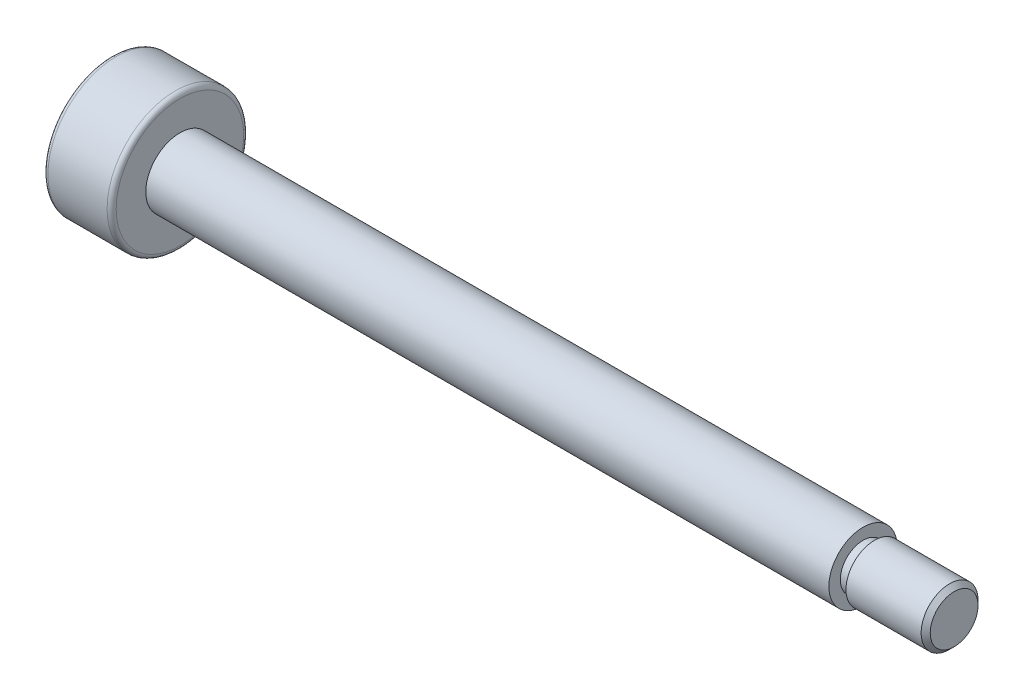
SolidWorks part; units mm, degrees
ref_plane "前视基准面" through (0, 0, 0) normal (0, 0, 1) x (1, 0, 0)
ref_plane "上视基准面" through (0, 0, 0) normal (0, 1, 0) x (1, 0, 0)
ref_plane "右视基准面" through (0, 0, 0) normal (1, 0, 0) x (0, 0, -1)
sketch "草图1" plane through (0, 0, 0) normal (0, 0, 1) x (1, 0, 0)
  line L0 (-18.5, 0) -> (18.5, 0) construction
  line L1 (-18.5, 0) -> (-18.5, 3)
  line L2 (-18.5, 3) -> (-15.5, 3)
  line L3 (-15.5, 3) -> (-15.5, 1.5)
  line L4 (-15.5, 1.5) -> (14.5, 1.5)
  line L5 (14.5, 1.5) -> (14.5, 1.25)
  line L6 (14.5, 1.25) -> (18.5, 1.25)
  line L7 (18.5, 1.25) -> (18.5, 0)
  line L8 (-18.5, 0) -> (18.5, 0)
  dimension "D1" = 3
  dimension "D2" = 6
  dimension "D3" = 2.5
  dimension "D4" = 4
  dimension "D5" = 30
  dimension "D6" = 3
revolve "旋转1" add sketch "草图1" angle 360 about L0
fillet "圆角1" radius 0.2 2 edges at (-15.5, 0, 3) (-18.5, 0, 3)
chamfer "倒角1" distance 0.2 angle 45 1 edges at (18.5, 0, 1.25)
sketch "草图3" plane through (0, 0, 0) normal (0, 0, 1) x (1, 0, 0)
  line L0 (14.5, 0) -> (18.3, 0) construction
  line L1 (14.5, -1.25) -> (14.5, 1.25) construction
  line L2 (18.3, 1.25) -> (18.3, -1.25) construction
  line L3 (14.5, -1.5) -> (14.5, 1.5) construction
  line L4 (14.5, 1.25) -> (15, 1.25)
  line L5 (14.5, 1.25) -> (14.5, 1)
  line L6 (14.5, 1) -> (15, 1)
  line L7 (15, 1.25) -> (15, 1)
  line L8 (18.3, 1.25) -> (14.5, 1.25) construction
  dimension "D1" = 2
  dimension "D2" = 0.5
revolve "切除-旋转1" cut sketch "草图3" angle 360 about L0
sketch "草图4" plane through (-18.5, 0, 0) normal (-1, 0, 0) x (0, 0, 1)
  line L1 (1.7321, 0) -> (0.866, 1.5)
  line L2 (0.866, 1.5) -> (-0.866, 1.5)
  line L3 (-0.866, 1.5) -> (-1.7321, 0)
  line L4 (-1.7321, 0) -> (-0.866, -1.5)
  line L5 (-0.866, -1.5) -> (0.866, -1.5)
  line L6 (0.866, -1.5) -> (1.7321, 0)
  circle A0 centre (0, 0) radius 1.5 construction
  dimension "D1" = 3
extrude "切除-拉伸1" cut sketch "草图4" against normal blind 2
